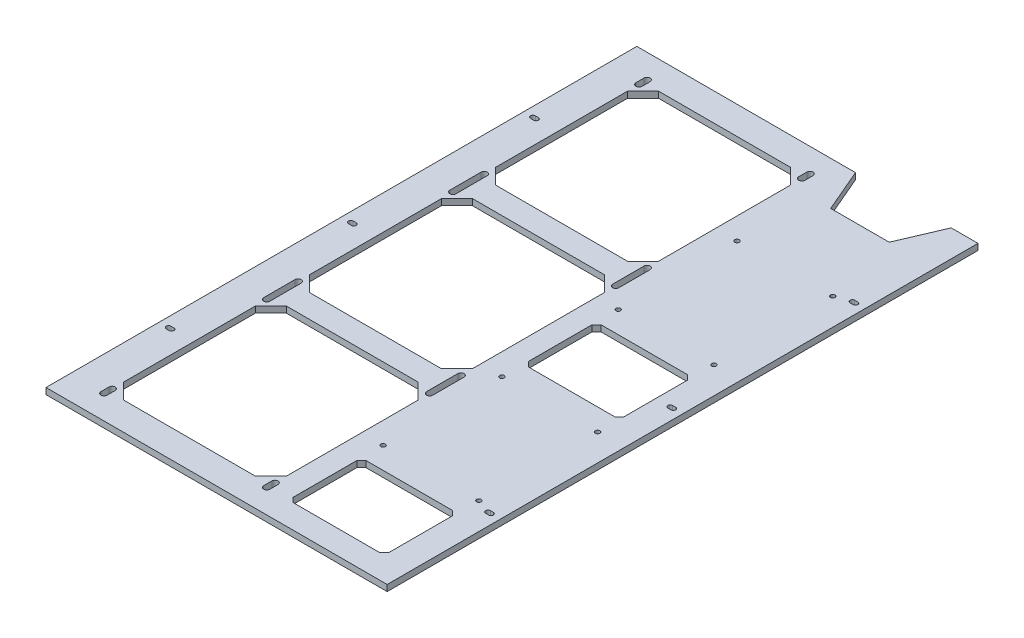
SolidWorks part; units mm, degrees
ref_plane "前基準面" through (0, 0, 0) normal (0, 0, 1) x (1, 0, 0)
ref_plane "上基準面" through (0, 0, 0) normal (0, 1, 0) x (1, 0, 0)
ref_plane "右基準面" through (0, 0, 0) normal (1, 0, 0) x (0, 0, -1)
sketch "草圖1" plane through (0, 0, 0) normal (0, 1, 0) x (1, 0, 0)
  line L1 (-110, 190.5) -> (110, 190.5)
  line L2 (-110, 190.5) -> (-110, -190.5)
  line L3 (-110, -190.5) -> (110, -190.5)
  line L4 (110, 190.5) -> (110, -190.5)
  line L5 (-110, 190.5) -> (110, -190.5) construction
  line L6 (-110, -190.5) -> (110, 190.5) construction
  point P0 (0, 0)
  dimension "D1" = 220
  dimension "D2" = 381
extrude "填料-伸長1" add sketch "草圖1" along normal blind 4
sketch "草圖4" plane through (0, 4, 0) normal (0, 1, 0) x (1, 0, 0)
  line L0 (-110, -190.5) -> (110, -190.5) construction
  line L1 (-103, -117.5) -> (-93, -117.5) construction
  line L2 (-110, 190.5) -> (-110, -190.5) construction
  line L4 (103, -117.5) -> (93, -117.5) construction
  line L5 (103, -117.5) -> (103, 0) construction
  line L6 (110, -190.5) -> (110, 190.5) construction
  line L7 (-103, -117.5) -> (-103, 0) construction
  point P0 (-103, -117.5)
  point P10 (-93, -117.5)
  point P11 (93, -117.5)
  point P15 (103, -117.5)
  point P21 (93, 0)
  point P22 (93, 117.5)
  point P23 (103, 0)
  point P24 (-93, 0)
  point P25 (-93, 117.5)
  point P26 (-103, 0)
  point P27 (-103, 117.5)
  point P32 (103, 117.5)
  dimension "D3" = 2
  dimension "D4" = 3
  dimension "D5" = 7
  dimension "D6" = 10
  dimension "D9" = 3
  dimension "D10" = 10
  dimension "D11" = 7
  dimension "D12" = 117.5
  dimension "D2" = 73
  dimension "D13" = 117.5
  dimension "D7" = 73
  dimension "D8" = 2
hole_wizard "Ø3.0mm 定位孔1" positions "3D草圖5" profile "草圖14" hole size "Ø3.0" standard "GB" end condition through all
sketch3d "3D草圖5"
  point P0 (-103, 4, -117.5)
  point P3 (103, 4, -117.5)
  point P6 (103, 4, 0)
  point P9 (-103, 4, 0)
  point P12 (103, 4, 117.5)
  point P15 (-103, 4, 117.5)
sketch "草圖14" plane through (-103, 4, -117.5) normal (1, 0, 0) x (0, 0, 1)
  line L0 (0, 0) -> (0, 4)
  line L1 (0, 4) -> (1.5, 4)
  line L2 (1.5, 4) -> (1.5, 0)
  line L5 (1.5, 0) -> (0, 0)
  line L11 (0, -6.35) -> (0, 107.95) construction
  dimension "貫穿孔直徑" = 3
  dimension "貫穿孔深度" = 4
sketch "草圖19" plane through (0, 4, 0) normal (0, 1, 0) x (1, 0, 0)
  line L0 (-88, 172.5) -> (-88, 67.5) construction
  line L1 (-88, 172.5) -> (17, 172.5) construction
  line L2 (17, 67.5) -> (17, -52.5) construction
  line L3 (-110, 190.5) -> (-110, -190.5) construction
  line L4 (110, 190.5) -> (-110, 190.5) construction
  line L5 (31, 37.5) -> (92.72, 37.5) construction
  line L6 (31, 37.5) -> (31, 114.1) construction
  line L7 (92.72, 114.1) -> (92.72, 37.5) construction
  line L8 (31, 114.1) -> (31, 190.5) construction
  line L9 (92.72, -128.1) -> (92.72, -175.1)
  line L10 (31, 128.1) -> (92.72, 128.1)
  line L11 (31, 128.1) -> (31, 175.1)
  line L12 (92.72, 23.5) -> (31, 23.5)
  line L13 (92.72, 23.5) -> (92.72, -23.5)
  line L14 (92.72, -23.5) -> (31, -23.5)
  line L15 (31, 23.5) -> (31, -23.5)
  line L16 (31, 175.1) -> (92.72, 175.1)
  line L17 (92.72, 128.1) -> (92.72, 175.1)
  line L18 (92.72, -128.1) -> (31, -128.1)
  line L19 (31, -128.1) -> (31, -175.1)
  line L20 (92.72, -175.1) -> (31, -175.1)
  line L21 (92.72, 37.5) -> (92.72, -114.1) construction
  line L22 (31, 162.5) -> (31, 190.5)
  line L23 (31, 162.5) -> (92.72, 162.5) construction
  line L24 (92.72, 162.5) -> (92.72, 190.5)
  line L32 (92.72, 190.5) -> (80.72, 162.5)
  line L33 (31, 190.5) -> (43, 162.5)
  line L34 (31, 190.5) -> (92.72, 190.5)
  line L35 (43, 162.5) -> (80.72, 162.5)
  point P0 (-88, 172.5)
  point P2 (31, 152.3)
  point P3 (-88, 52.5)
  point P4 (17, 172.5)
  point P5 (17, 67.5)
  point P6 (-88, 67.5)
  point P9 (17, -52.5)
  point P10 (-88, -52.5)
  point P11 (-88, -67.5)
  point P12 (17, -172.5)
  point P13 (-88, -172.5)
  point P21 (31, 37.5)
  point P23 (92.72, 37.5)
  point P24 (92.72, 114.1)
  point P25 (31, 114.1)
  point P29 (17, -67.5)
  point P30 (17, 52.5)
  point P32 (92.72, -37.5)
  point P41 (31, -114.1)
  point P42 (92.72, -114.1)
  point P43 (31, -37.5)
  line M19 (110, 190.5) -> (-110, 190.5)
  dimension "D3" = 105
  dimension "D4" = 105
  dimension "D6" = 120
  dimension "D7" = 22
  dimension "D8" = 18
  dimension "D11" = 61.72
  dimension "D12" = 76.6
  dimension "D13" = 14
  dimension "D14" = 47
  dimension "D15" = 14
  dimension "D16" = 47
  dimension "D17" = 14
  dimension "D19" = 151.6
  dimension "D20" = 15.4
  dimension "D21" = 105
  dimension "D22" = 15
  dimension "D23" = 12
  dimension "D24" = 12
  dimension "D1" = 2
  dimension "D2" = 2
  dimension "D5" = 3
  dimension "D9" = 2
  dimension "D10" = 2
  dimension "D18" = 2
sketch "草圖24" plane through (0, 4, 0) normal (0, 1, 0) x (1, 0, 0)
  line L0 (17, 169.9) -> (17, 175.1) construction
  line L1 (34, 175.1) -> (89.72, 175.1)
  line L2 (31, 172.1) -> (31, 131.1)
  line L3 (34, 128.1) -> (89.72, 128.1)
  line L4 (92.72, 172.1) -> (92.72, 131.1)
  line L5 (34, 23.5) -> (89.72, 23.5)
  line L6 (31, 20.5) -> (31, -20.5)
  line L7 (34, -23.5) -> (89.72, -23.5)
  line L8 (92.72, 20.5) -> (92.72, -20.5)
  line L9 (34, -128.1) -> (89.72, -128.1)
  line L10 (31, -131.1) -> (31, -172.1)
  line L11 (34, -175.1) -> (89.72, -175.1)
  line L12 (92.72, -131.1) -> (92.72, -172.1)
  line L13 (15, 169.9) -> (15, 175.1)
  line L14 (19, 169.9) -> (19, 175.1)
  line L15 (-88, 169.9) -> (-88, 175.1) construction
  line L16 (-90, 169.9) -> (-90, 175.1)
  line L17 (-86, 169.9) -> (-86, 175.1)
  line L18 (17, 169.9) -> (-88, 169.9) construction
  line L19 (-88, 70.1) -> (-88, 49.9) construction
  line L20 (89.72, 175.1) -> (92.72, 172.1)
  line L21 (-88, 172.5) -> (-88, 67.5) construction
  line L22 (-86, 70.1) -> (-86, 49.9)
  line L23 (-90, 70.1) -> (-90, 49.9)
  line L24 (17, 70.1) -> (17, 49.9) construction
  line L25 (19, 70.1) -> (19, 49.9)
  line L26 (15, 70.1) -> (15, 49.9)
  line L27 (17, -49.9) -> (17, -70.1) construction
  line L28 (19, -49.9) -> (19, -70.1)
  line L29 (15, -49.9) -> (15, -70.1)
  line L30 (-88, -49.9) -> (-88, -70.1) construction
  line L31 (-86, -49.9) -> (-86, -70.1)
  line L32 (-90, -49.9) -> (-90, -70.1)
  line L33 (-88, 70.1) -> (17, 70.1) construction
  line L34 (-88, 70.1) -> (-88, -49.9) construction
  line L35 (17, -169.9) -> (17, -175.1) construction
  line L36 (19, -169.9) -> (19, -175.1)
  line L37 (15, -169.9) -> (15, -175.1)
  line L38 (-88, -169.9) -> (-88, -175.1) construction
  line L39 (-86, -169.9) -> (-86, -175.1)
  line L40 (-90, -169.9) -> (-90, -175.1)
  line L41 (17, -169.9) -> (-88, -169.9) construction
  line L42 (7, 172.5) -> (17, 162.5)
  line L43 (-78, 172.5) -> (7, 172.5)
  line L44 (-88, 162.5) -> (-88, 77.5)
  line L45 (-78, 67.5) -> (7, 67.5)
  line L46 (17, 162.5) -> (17, 77.5)
  line L47 (-88, 162.5) -> (-78, 172.5)
  line L48 (-88, 77.5) -> (-78, 67.5)
  line L49 (17, 77.5) -> (7, 67.5)
  line L50 (-88, 42.5) -> (-88, -42.5)
  line L51 (-88, -42.5) -> (-78, -52.5)
  line L52 (-88, 42.5) -> (-78, 52.5)
  line L53 (-78, 52.5) -> (7, 52.5)
  line L54 (7, 52.5) -> (17, 42.5)
  line L55 (17, 42.5) -> (17, -42.5)
  line L56 (17, -42.5) -> (7, -52.5)
  line L57 (-78, -52.5) -> (7, -52.5)
  line L58 (-88, -77.5) -> (-88, -162.5)
  line L59 (-88, -162.5) -> (-78, -172.5)
  line L60 (-88, -77.5) -> (-78, -67.5)
  line L61 (-78, -67.5) -> (7, -67.5)
  line L62 (7, -67.5) -> (17, -77.5)
  line L63 (17, -77.5) -> (17, -162.5)
  line L64 (17, -162.5) -> (7, -172.5)
  line L65 (-78, -172.5) -> (7, -172.5)
  line L66 (-88, 162.5) -> (-88, 42.5) construction
  line L67 (89.72, 128.1) -> (92.72, 131.1)
  line L68 (31, 172.1) -> (34, 175.1)
  line L69 (31, 131.1) -> (34, 128.1)
  line L70 (89.72, 23.5) -> (92.72, 20.5)
  line L71 (31, 20.5) -> (34, 23.5)
  line L72 (31, -20.5) -> (34, -23.5)
  line L73 (89.72, -23.5) -> (92.72, -20.5)
  line L74 (89.72, -128.1) -> (92.72, -131.1)
  line L75 (31, -131.1) -> (34, -128.1)
  line L76 (31, -172.1) -> (34, -175.1)
  line L77 (89.72, -175.1) -> (92.72, -172.1)
  arc A0 (15, 169.9) -> (19, 169.9) centre (17, 169.9) ccw
  arc A1 (19, 175.1) -> (15, 175.1) centre (17, 175.1) ccw
  arc A2 (-90, 169.9) -> (-86, 169.9) centre (-88, 169.9) ccw
  arc A3 (-86, 175.1) -> (-90, 175.1) centre (-88, 175.1) ccw
  arc A4 (-86, 70.1) -> (-90, 70.1) centre (-88, 70.1) ccw
  arc A5 (-90, 49.9) -> (-86, 49.9) centre (-88, 49.9) ccw
  arc A6 (19, 70.1) -> (15, 70.1) centre (17, 70.1) ccw
  arc A7 (15, 49.9) -> (19, 49.9) centre (17, 49.9) ccw
  arc A8 (19, -49.9) -> (15, -49.9) centre (17, -49.9) ccw
  arc A9 (15, -70.1) -> (19, -70.1) centre (17, -70.1) ccw
  arc A10 (-86, -49.9) -> (-90, -49.9) centre (-88, -49.9) ccw
  arc A11 (-90, -70.1) -> (-86, -70.1) centre (-88, -70.1) ccw
  arc A12 (19, -169.9) -> (15, -169.9) centre (17, -169.9) ccw
  arc A13 (15, -175.1) -> (19, -175.1) centre (17, -175.1) ccw
  arc A14 (-86, -169.9) -> (-90, -169.9) centre (-88, -169.9) ccw
  arc A15 (-90, -175.1) -> (-86, -175.1) centre (-88, -175.1) ccw
  point P0 (31, 175.1)
  point P1 (92.72, 128.1)
  point P2 (31, 128.1)
  point P3 (92.72, 175.1)
  point P6 (31, 23.5)
  point P7 (92.72, -23.5)
  point P8 (31, -23.5)
  point P9 (92.72, 23.5)
  point P12 (31, -128.1)
  point P13 (92.72, -175.1)
  point P14 (31, -175.1)
  point P15 (92.72, -128.1)
  point P20 (17, 172.5)
  point P30 (-88, 172.5)
  point P39 (-88, 60)
  point P48 (17, -172.5)
  point P51 (17, 60)
  point P58 (17, -60)
  point P65 (-88, -60)
  point P78 (-88, 172.5)
  point P79 (17, 67.5)
  point P82 (-88, -172.5)
  point P89 (-88, 67.5)
  point P90 (17, 172.5)
  dimension "D1" = 2
  dimension "D10" = 2
  dimension "D11" = 2
  dimension "D3" = 105
  dimension "D4" = 2.6
  dimension "D5" = 2.6
  dimension "D8" = 105
  dimension "D9" = 120
  dimension "D13" = 105
  dimension "D15" = 120
  dimension "D2" = 2
  dimension "D6" = 2
  dimension "D7" = 2
  dimension "D12" = 2
  dimension "D14" = 3
extrude "除料-伸長7" cut sketch "草圖24" against normal through all contours L49 L46 L42 L43 L47 L44 L48 L45 | L51 L57 L56 L55 L54 L53 L52 L50 | L59 L65 L64 L63 L62 L61 L60 L58 | L11 L77 L12 L74 L9 L75 L10 L76 | L7 L73 L8 L70 L5 L71 L6 L72 | L40 A15 L39 A14 | L29 A9 L28 A8 | L32 A11 L31 A10 | L14 A1 L13 A0 | L17 A3 L16 A2 | L36 A13 L37 A12 | L25 A7 L26 A6 | L22 A5 L23 A4
extrude "除料-伸長8" cut sketch "草圖19" against normal through all contours L33 L16 L32 M19 | L33 L35 L32 L16
hole_wizard "Ø2.9 (2.9) 直徑孔2" positions "草圖22" profile "草圖23" hole size "Ø2.9" standard "GB" end condition through all
sketch "草圖22" plane through (0, 4, 0) normal (0, 1, 0) x (1, 0, 0)
  point P0 (31, 114.1)
  point P3 (92.72, 114.1)
  point P6 (31, 37.5)
  point P9 (92.72, 37.5)
  point P12 (31, -37.5)
  point P15 (92.72, -37.5)
  point P18 (31, -114.1)
  point P21 (92.72, -114.1)
sketch "草圖23" plane through (31, 4, -114.1) normal (1, 0, 0) x (0, 0, 1)
  line L0 (0, 0) -> (0, 4)
  line L1 (0, 4) -> (1.45, 4)
  line L2 (1.45, 4) -> (1.45, 0)
  line L5 (1.45, 0) -> (0, 0)
  line L11 (0, -6.35) -> (0, 107.95) construction
  dimension "貫穿孔直徑" = 2.9
  dimension "貫穿孔深度" = 4
sketch "草圖18" plane through (0, 4, 0) normal (0, 1, 0) x (1, 0, 0)
  line L0 (-104, 117.5) -> (-102, 117.5) construction
  line L1 (-104, 119) -> (-102, 119)
  line L2 (-104, 116) -> (-102, 116)
  line L3 (102, 117.5) -> (104, 117.5) construction
  line L4 (102, 119) -> (104, 119)
  line L5 (102, 116) -> (104, 116)
  line L6 (102, 0) -> (104, 0) construction
  line L7 (102, 1.5) -> (104, 1.5)
  line L8 (102, -1.5) -> (104, -1.5)
  line L9 (102, -117.5) -> (104, -117.5) construction
  line L10 (102, -116) -> (104, -116)
  line L11 (102, -119) -> (104, -119)
  line L12 (-104, 0) -> (-102, 0) construction
  line L13 (-104, 1.5) -> (-102, 1.5)
  line L14 (-104, -1.5) -> (-102, -1.5)
  line L15 (-104, -117.5) -> (-102, -117.5) construction
  line L16 (-104, -116) -> (-102, -116)
  line L17 (-104, -119) -> (-102, -119)
  line L18 (-104, 117.5) -> (102, 117.5) construction
  line L19 (-104, 117.5) -> (-104, 0) construction
  arc A0 (-104, 119) -> (-104, 116) centre (-104, 117.5) ccw
  arc A1 (-102, 116) -> (-102, 119) centre (-102, 117.5) ccw
  arc A2 (102, 119) -> (102, 116) centre (102, 117.5) ccw
  arc A3 (104, 116) -> (104, 119) centre (104, 117.5) ccw
  arc A4 (102, 1.5) -> (102, -1.5) centre (102, 0) ccw
  arc A5 (104, -1.5) -> (104, 1.5) centre (104, 0) ccw
  arc A6 (102, -116) -> (102, -119) centre (102, -117.5) ccw
  arc A7 (104, -119) -> (104, -116) centre (104, -117.5) ccw
  arc A8 (-104, 1.5) -> (-104, -1.5) centre (-104, 0) ccw
  arc A9 (-102, -1.5) -> (-102, 1.5) centre (-102, 0) ccw
  arc A10 (-104, -116) -> (-104, -119) centre (-104, -117.5) ccw
  arc A11 (-102, -119) -> (-102, -116) centre (-102, -117.5) ccw
  point P2 (-103, 117.5)
  point P13 (103, 117.5)
  point P20 (103, 0)
  point P27 (103, -117.5)
  point P34 (-103, 0)
  point P41 (-103, -117.5)
  dimension "D2" = 1.5
  dimension "D1" = 2
  dimension "D5" = 206
  dimension "D6" = 117.5
  dimension "D3" = 2
  dimension "D4" = 3
extrude "除料-伸長5" cut sketch "草圖18" against normal through all
